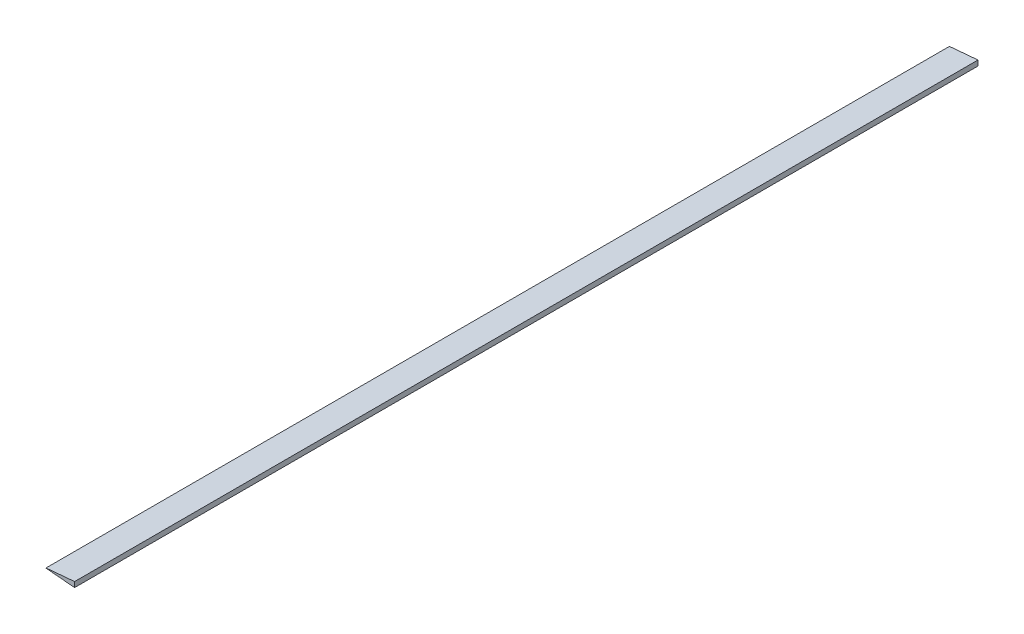
SolidWorks part; units mm, degrees
ref_plane "Front Plane" through (0, 0, 0) normal (0, 0, 1) x (1, 0, 0)
ref_plane "Top Plane" through (0, 0, 0) normal (0, 1, 0) x (1, 0, 0)
ref_plane "Right Plane" through (0, 0, 0) normal (1, 0, 0) x (0, 0, -1)
sketch "Sketch1" plane through (0, 0, 0) normal (0, 0, 1) x (1, 0, 0)
  line L0 (-62.4953, 2.4526) -> (-62.4953, -2.4526)
  line L1 (-89.279, 0.0844) -> (-89.279, -0.0844)
  spline S0 degree 3 poles (-62.4953, 2.4526) (-62.5955, 2.4455) (-64.084, 2.3405) (-66.8784, 2.1241) (-70.7828, 1.8124) (-74.4007, 1.5063) (-77.6925, 1.2153) (-80.6222, 0.9456) (-83.1576, 0.7036) (-85.271, 0.4956) (-86.9393, 0.3271) (-88.1441, 0.2031) (-88.8723, 0.1271) (-89.1975, 0.0929) (-89.279, 0.0844) knots 0 0 0 0 0.011212 0.166483 0.312686 0.448211 0.571563 0.681381 0.776452 0.855723 0.918312 0.963525 0.990856 1 1 1 1
  spline S1 degree 3 poles (-62.4953, -2.4526) (-62.5955, -2.4455) (-64.084, -2.3405) (-66.8784, -2.1241) (-70.7828, -1.8124) (-74.4007, -1.5063) (-77.6925, -1.2153) (-80.6222, -0.9456) (-83.1576, -0.7036) (-85.271, -0.4956) (-86.9393, -0.3271) (-88.1441, -0.2031) (-88.8723, -0.1271) (-89.1975, -0.0929) (-89.279, -0.0844) knots 0 0 0 0 0.011212 0.166483 0.312686 0.448211 0.571563 0.681381 0.776452 0.855723 0.918312 0.963525 0.990856 1 1 1 1
extrude "Boss-Extrude1" add sketch "Sketch1" along normal mid plane 845.8
